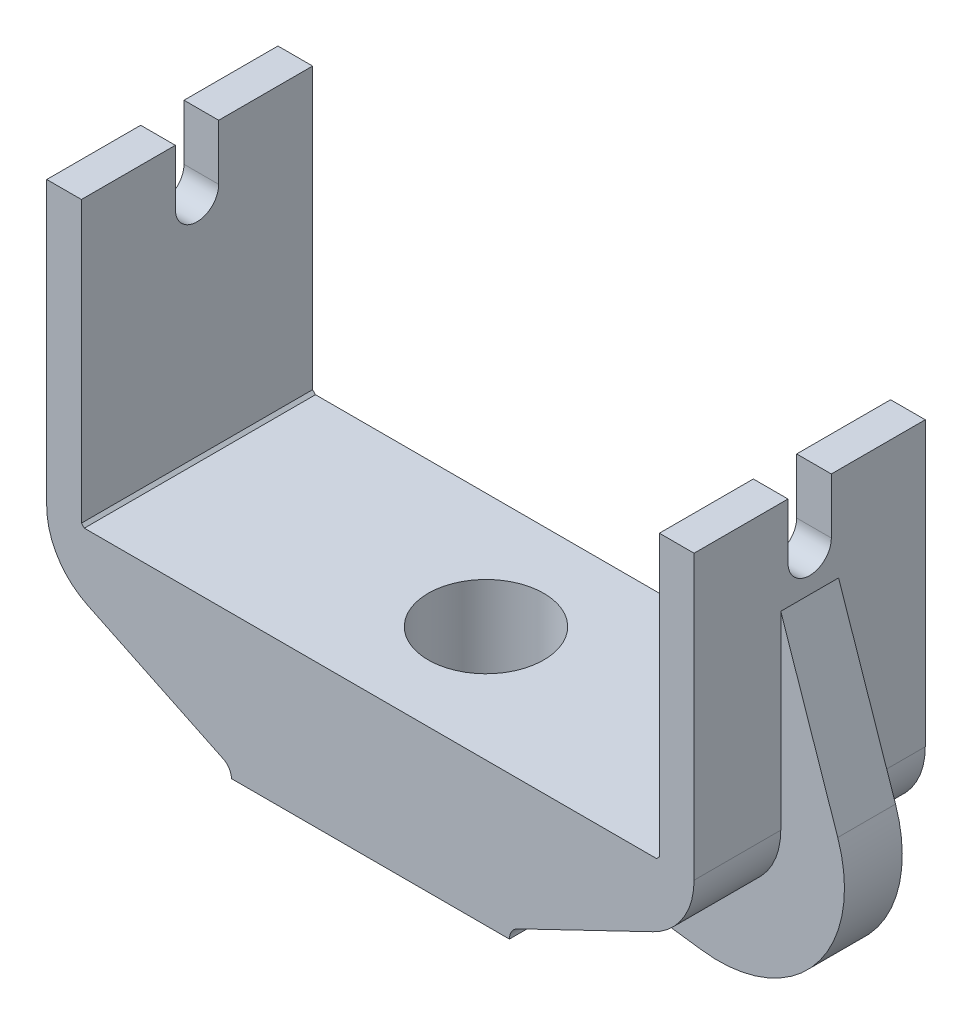
SolidWorks part; units mm, degrees
ref_plane "Front Plane" through (0, 0, 0) normal (0, 0, 1) x (1, 0, 0)
ref_plane "Top Plane" through (0, 0, 0) normal (0, 1, 0) x (1, 0, 0)
ref_plane "Right Plane" through (0, 0, 0) normal (1, 0, 0) x (0, 0, -1)
sketch "Sketch1" plane through (0, 0, 0) normal (0, 0, 1) x (1, 0, 0)
  line L0 (0, 0) -> (2.405, 0)
  line L1 (2.5466, 0.2253) -> (4.8919, 1.3536)
  line L2 (5.6, 2.48) -> (5.6, 7.38)
  line L3 (5.6, 7.38) -> (5, 7.38)
  line L4 (5, 7.38) -> (5, 2.48)
  line L5 (5, 2.48) -> (0, 2.48)
  line L6 (0, 2.48) -> (0, 0)
  arc A0 (2.405, 0) -> (2.5466, 0.2253) centre (2.655, 0) cw
  arc A1 (4.8919, 1.3536) -> (5.6, 2.48) centre (4.35, 2.48) ccw
  dimension "D1" = 2.405
  dimension "D2" = 0.25
  dimension "D4" = 1.25
  dimension "D3" = 2.48
  dimension "D5" = 4.9
  dimension "D6" = 0
  dimension "D7" = 5
  dimension "D8" = 7.38
  dimension "D9" = 0.6
extrude "Boss-Extrude1" add sketch "Sketch1" along normal mid plane 4
mirror "Mirror1" about plane through (0, 0, 0) normal (1, 0, 0) of "Boss-Extrude1"
chamfer "Chamfer1" distance 0.05 angle 45 2 edges at (5, 2.48, 0) (-5, 2.48, 0)
sketch "Sketch3" plane through (0, 0, 0) normal (0, 0, 1) x (1, 0, 0)
  line L0 (2.5466, 0.2253) -> (4.2335, 0)
  line L1 (6.5859, 2.8632) -> (5.6, 5.76)
  line L2 (5.6, 2.48) -> (5.6, 7.38) construction
  line L3 (-2.405, 0) -> (2.405, 0) construction
  line L4 (5.6, 7.38) -> (5, 7.38) construction
  line L5 (2.5466, 0.2253) -> (4.8919, 1.3536) construction
  line L6 (2.5466, 0.2253) -> (4.8919, 1.3536)
  line L7 (5.6, 2.48) -> (5.6, 5.76)
  arc A0 (4.2335, 0) -> (6.5859, 2.8632) centre (4.5221, 2.1608) ccw
  arc A1 (4.8919, 1.3536) -> (5.6, 2.48) centre (4.35, 2.48) ccw construction
  arc A2 (4.8919, 1.3536) -> (5.6, 2.48) centre (4.35, 2.48) ccw
  dimension "D1" = 2.18
  dimension "D2" = 1.62
  dimension "D3" = 3.06
extrude "Boss-Extrude2" add sketch "Sketch3" along normal mid plane 1
mirror "Mirror2" about plane through (0, 0, 0) normal (1, 0, 0) of "Boss-Extrude2"
sketch "Sketch4" plane through (5.6, 0, 0) normal (1, 0, 0) x (0, 0, -1)
  line L0 (-2, 0) -> (2, 0) construction
  line L1 (0.375, 6.42) -> (0.375, 7.38)
  line L2 (-2, 7.38) -> (2, 7.38) construction
  line L3 (-0.375, 6.42) -> (-0.375, 7.38)
  line L4 (-0.375, 7.38) -> (0.375, 7.38)
  arc A0 (-0.375, 6.42) -> (0.375, 6.42) centre (0, 6.42) ccw
  dimension "D1" = 0.75
  dimension "D2" = 6.42
extrude "Cut-Extrude1" cut sketch "Sketch4" against normal through all
sketch "Sketch5" plane through (0, 2.48, 0) normal (0, 1, 0) x (1, 0, 0)
  circle A0 centre (0, 0) radius 1
  dimension "D1" = 2
extrude "Cut-Extrude2" cut sketch "Sketch5" against normal through all
